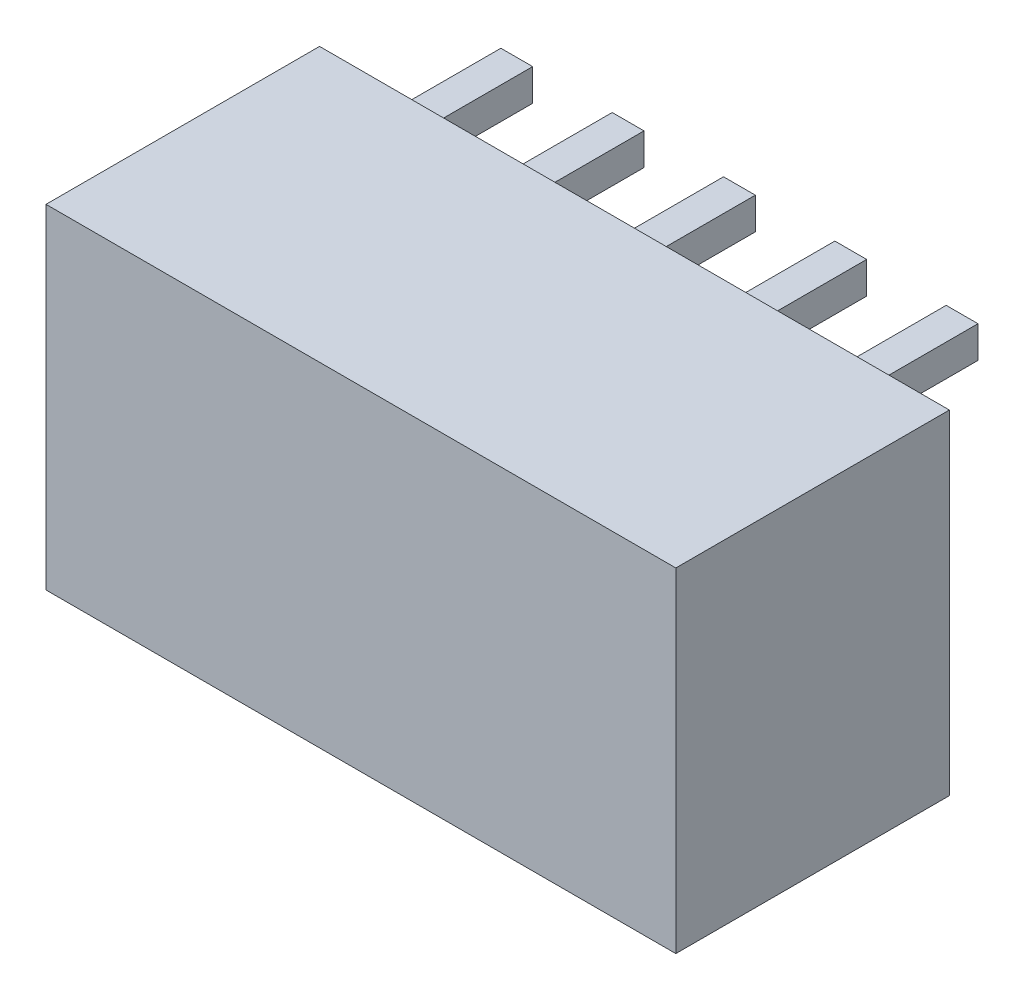
SolidWorks part; units mm, degrees
ref_plane "Спереди" through (0, 0, 0) normal (0, 0, 1) x (1, 0, 0)
ref_plane "Сверху" through (0, 0, 0) normal (0, 1, 0) x (1, 0, 0)
ref_plane "Справа" through (0, 0, 0) normal (1, 0, 0) x (0, 0, -1)
sketch "Эскиз1" plane through (0, 0, 0) normal (0, 0, 1) x (1, 0, 0)
  line L1 (-9.9, -5.25) -> (9.9, -5.25)
  line L2 (-9.9, -5.25) -> (-9.9, 5.25)
  line L3 (-9.9, 5.25) -> (9.9, 5.25)
  line L4 (9.9, -5.25) -> (9.9, 5.25)
  line L5 (-9.9, -5.25) -> (9.9, 5.25) construction
  line L6 (-9.9, 5.25) -> (9.9, -5.25) construction
  point P0 (0, 0)
  dimension "D1" = 19.8
  dimension "D2" = 10.5
extrude "Бобышка-Вытянуть1" add sketch "Эскиз1" along normal blind 8.6
sketch "Эскиз2" plane through (0, -5.25, 0) normal (0, -1, 0) x (1, 0, 0)
  line L0 (-8.9, 6.6) -> (8.9, 6.6)
  line L1 (8.9, 6.6) -> (8.9, 0.2)
  line L2 (8.9, 0.2) -> (6.7, 0.2)
  line L3 (6.7, 0.2) -> (6.7, 1.8)
  line L4 (6.7, 1.8) -> (-5.1, 1.8)
  line L5 (-5.1, 1.8) -> (-5.1, 0.2)
  line L6 (-5.1, 0.2) -> (-7.3, 0.2)
  line L7 (-8.9, 6.6) -> (-8.9, 1.8)
  line L8 (-8.9, 1.8) -> (-7.3, 1.8)
  line L9 (-7.3, 1.8) -> (-7.3, 0.2)
  line L10 (9.9, 8.6) -> (9.9, 0) construction
  line L11 (-9.9, 8.6) -> (-9.9, 0) construction
  line L12 (-9.9, 8.6) -> (9.9, 8.6) construction
  dimension "D1" = 4.8
  dimension "D2" = 6.4
  dimension "D3" = 2.2
  dimension "D4" = 2.2
  dimension "D5" = 3.2
  dimension "D6" = 4.8
  dimension "D7" = 1
  dimension "D8" = 2
extrude "Вырез-Вытянуть1" cut sketch "Эскиз2" against normal blind 7
sketch "Эскиз3" plane through (0, 0, 0) normal (0, 0, -1) x (-1, 0, 0)
  line L0 (9.9, -5.25) -> (-9.9, -5.25) construction
  line L1 (7.5, 4.75) -> (6.5, 4.75)
  line L2 (7.5, 4.75) -> (7.5, 3.75)
  line L3 (7.5, 3.75) -> (6.5, 3.75)
  line L4 (6.5, 4.75) -> (6.5, 3.75)
  line L5 (7.5, 4.75) -> (6.5, 3.75) construction
  line L6 (7.5, 3.75) -> (6.5, 4.75) construction
  line L7 (9.9, 5.25) -> (9.9, -5.25) construction
  point P0 (7, 4.25)
  dimension "D1" = 1
  dimension "D2" = 9.5
  dimension "D3" = 2.9
extrude "Бобышка-Вытянуть2" add sketch "Эскиз3" along normal blind 3.6 and the other way blind 5
chamfer "Фаска1" distance 0.3 distance2 0.3 4 edges at (-6.5, 4.25, -3.6) (-7, 3.75, -3.6) (-7.5, 4.25, -3.6) (-7, 4.75, -3.6)
pattern_linear "Линейный массив1" count 5 spacing 3.5 along (1, 0, 0) of "Бобышка-Вытянуть2", "Фаска1"
equation "\"N\"= 5"
equation "\"D1@Эскиз1\"= ( \"N\" - 1 ) * 3.5 + 5.8"
equation "\"D1@Линейный массив1\"=\"N\""
